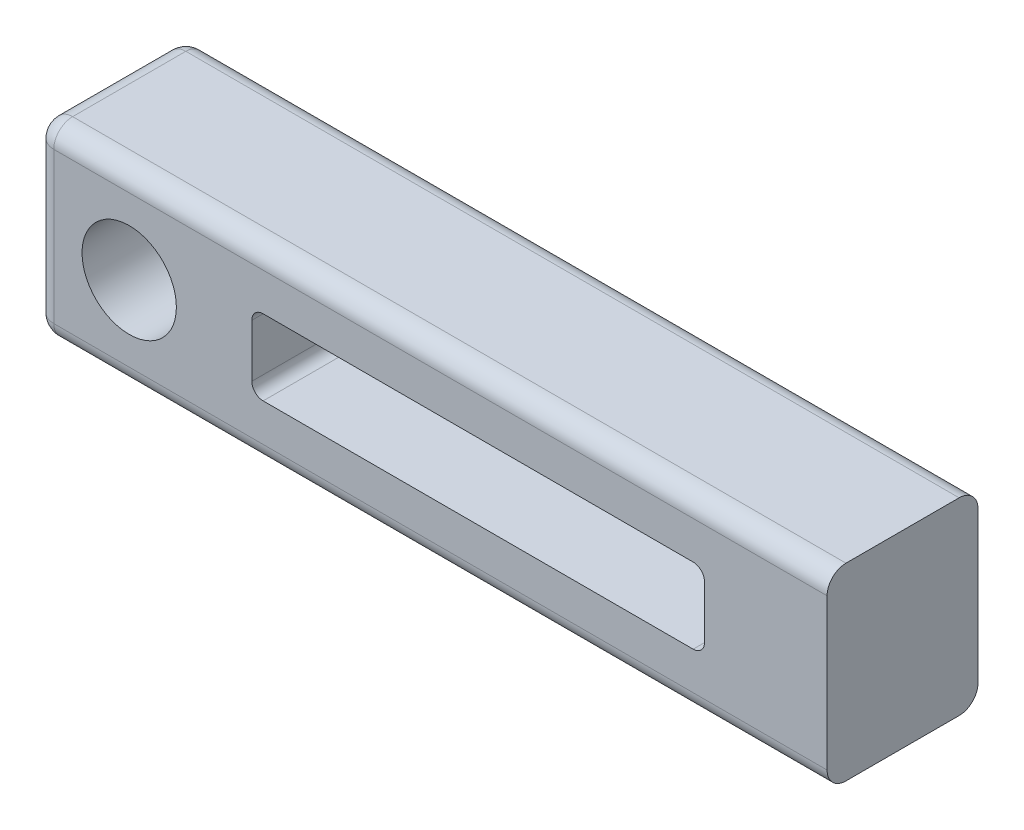
SolidWorks part; units mm, degrees
ref_plane "Alzado" through (0, 0, 0) normal (0, 0, 1) x (1, 0, 0)
ref_plane "Planta" through (0, 0, 0) normal (0, 1, 0) x (1, 0, 0)
ref_plane "Vista lateral" through (0, 0, 0) normal (1, 0, 0) x (0, 0, -1)
sketch "Croquis1" plane through (0, 0, 0) normal (0, 0, 1) x (1, 0, 0)
  line L0 (0, 0) -> (-25, 0) construction
  line L1 (-25, -25) -> (-25, 25)
  line L2 (-25, 25) -> (185, 25)
  line L3 (-25, -25) -> (185, -25)
  line L4 (185, 25) -> (185, -25)
  circle A0 centre (0, 0) radius 12.5
  dimension "D1" = 25
  dimension "D2" = 25
  dimension "D3" = 25
  dimension "D4" = 210
extrude "Saliente-Extruir1" add sketch "Croquis1" along normal blind 40
fillet "Redondeo1" radius 5 8 edges at (-25, 25, 20) (-25, 0, 40) (-25, -25, 20) (-25, 0, 0) (80, -25, 40) (80, -25, 0) (80, 25, 0) (80, 25, 40)
sketch "Croquis2" plane through (0, 0, 40) normal (0, 0, 1) x (1, 0, 0)
  line L0 (0, 0) -> (185, 0) construction
  line L1 (185, -20) -> (185, 20) construction
  line L2 (92.5, 0) -> (92.5, 10) construction
  line L3 (149.4992, 10) -> (35.5008, 10)
  line L4 (32.5008, 7) -> (32.5008, -7)
  line L5 (152.4992, 7) -> (152.4992, -7)
  line L6 (149.4992, -10) -> (35.5008, -10)
  arc A0 (32.5008, 7) -> (35.5008, 10) centre (35.5008, 7) cw
  arc A1 (152.4992, 7) -> (149.4992, 10) centre (149.4992, 7) ccw
  arc A2 (152.4992, -7) -> (149.4992, -10) centre (149.4992, -7) cw
  arc A3 (32.5008, -7) -> (35.5008, -10) centre (35.5008, -7) ccw
  point P16 (152.4992, 0)
  point P21 (32.5008, 0)
  dimension "D2" = 3
  dimension "D1" = 10
extrude "Cortar-Extruir1" cut sketch "Croquis2" against normal through all
